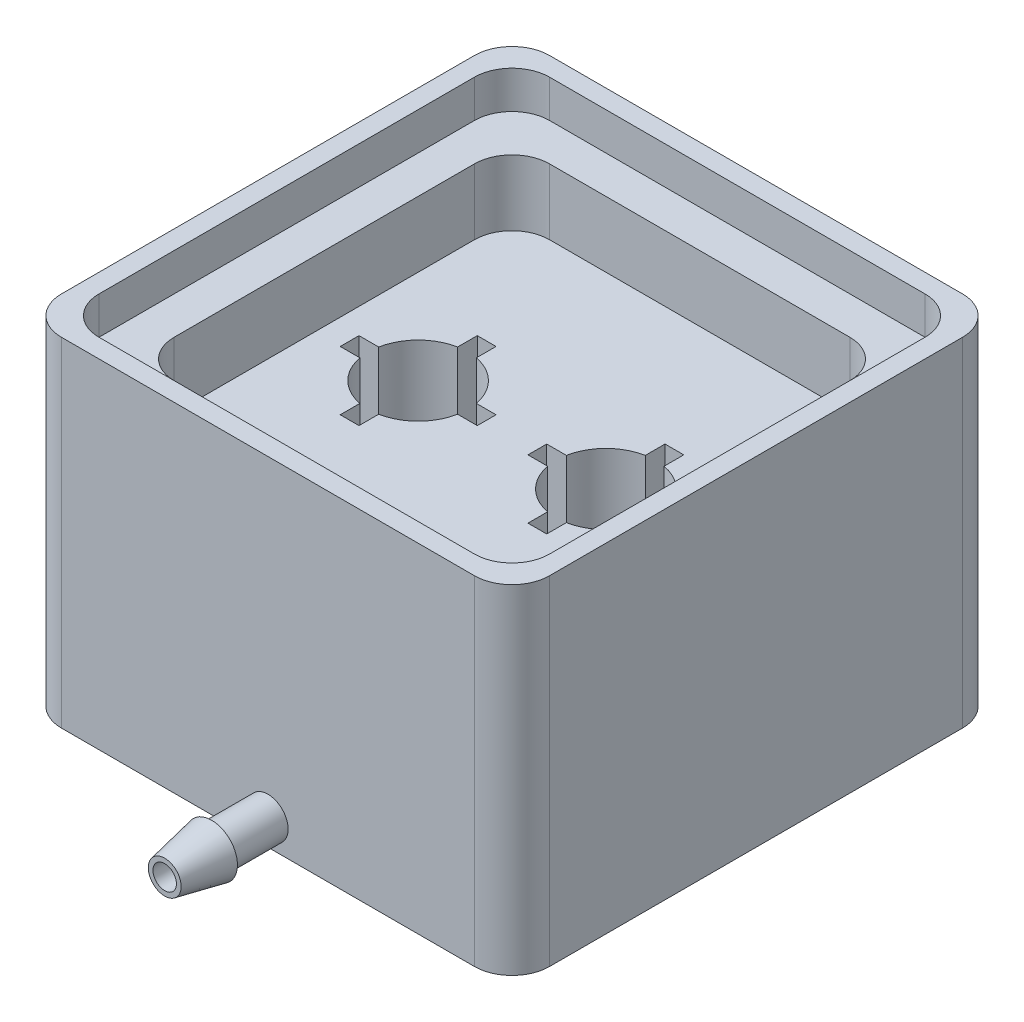
SolidWorks part; units mm, degrees
ref_plane "Front Plane" through (0, 0, 0) normal (0, 0, 1) x (1, 0, 0)
ref_plane "Top Plane" through (0, 0, 0) normal (0, 1, 0) x (1, 0, 0)
ref_plane "Right Plane" through (0, 0, 0) normal (1, 0, 0) x (0, 0, -1)
sketch "Sketch1" plane through (0, 0, 0) normal (0, 1, 0) x (1, 0, 0)
  line L0 (-5, 0) -> (5, 0) construction
  line L1 (-11, -13) -> (11, -13)
  line L2 (-13, -11) -> (-13, 11)
  line L3 (-11, 13) -> (11, 13)
  line L4 (13, -11) -> (13, 11)
  line L5 (-13, -13) -> (13, 13) construction
  line L6 (-13, 13) -> (13, -13) construction
  arc A0 (-13, 11) -> (-11, 13) centre (-11, 11) cw
  arc A1 (11, 13) -> (13, 11) centre (11, 11) cw
  arc A2 (-13, -11) -> (-11, -13) centre (-11, -11) ccw
  arc A3 (13, -11) -> (11, -13) centre (11, -11) cw
  circle A4 centre (5, 0) radius 2.65
  circle A5 centre (-5, 0) radius 2.65
  point P0 (0, 0)
  point P21 (0, 0)
  dimension "D3" = 2
  dimension "D4" = 2
  dimension "D6" = 5.3
  dimension "D7" = 5.3
  dimension "D1" = 26
  dimension "D2" = 26
  dimension "D5" = 10
extrude "Boss-Extrude1" add sketch "Sketch1" along normal blind 12.53
sketch "Sketch2" plane through (0, 12.53, 0) normal (0, 1, 0) x (1, 0, 0)
  line L0 (-5, 0) -> (5, 0) construction
  line L2 (-8.65, -0.5) -> (-1.35, -0.5)
  line L3 (-8.65, -0.5) -> (-8.65, 0.5)
  line L4 (-8.65, 0.5) -> (-1.35, 0.5)
  line L5 (-1.35, -0.5) -> (-1.35, 0.5)
  line L6 (-8.65, -0.5) -> (-1.35, 0.5) construction
  line L7 (-8.65, 0.5) -> (-1.35, -0.5) construction
  line L8 (-5.5, -3.65) -> (-4.5, -3.65)
  line L9 (-5.5, -3.65) -> (-5.5, 3.65)
  line L10 (-5.5, 3.65) -> (-4.5, 3.65)
  line L11 (-4.5, -3.65) -> (-4.5, 3.65)
  line L12 (-5.5, -3.65) -> (-4.5, 3.65) construction
  line L13 (-5.5, 3.65) -> (-4.5, -3.65) construction
  line L14 (4.5, -3.65) -> (5.5, -3.65)
  line L15 (4.5, -3.65) -> (4.5, 3.65)
  line L16 (4.5, 3.65) -> (5.5, 3.65)
  line L17 (5.5, -3.65) -> (5.5, 3.65)
  line L18 (4.5, -3.65) -> (5.5, 3.65) construction
  line L19 (4.5, 3.65) -> (5.5, -3.65) construction
  line L20 (1.35, -0.5) -> (8.65, -0.5)
  line L21 (1.35, -0.5) -> (1.35, 0.5)
  line L22 (1.35, 0.5) -> (8.65, 0.5)
  line L23 (8.65, -0.5) -> (8.65, 0.5)
  line L24 (1.35, -0.5) -> (8.65, 0.5) construction
  line L25 (1.35, 0.5) -> (8.65, -0.5) construction
  point P3 (0, 0)
  circle M15 centre (5, 0) radius 2.65
  circle M16 centre (-5, 0) radius 2.65
  dimension "D1" = 10
  dimension "D2" = 7.3
  dimension "D3" = 7.3
  dimension "D4" = 7.3
  dimension "D5" = 7.3
  dimension "D6" = 1
  dimension "D7" = 1
  dimension "D8" = 1
  dimension "D9" = 1
extrude "Cut-Extrude1" cut sketch "Sketch2" against normal blind 11.785 contours L17 L16 L15 M15 | L20 L23 L22 M15 | L14 L17 L15 M15 | L22 L21 L20 M15 | L2 L5 L4 M16 | L11 L10 L9 M16 | L4 L3 L2 M16 | L8 L11 L9 M16
sketch "Sketch3" plane through (0, 0, 0) normal (1, 0, 0) x (0, 0, -1)
  line L0 (-13, 0.3) -> (-16, 0.3)
  line L1 (-13, 12.53) -> (-13, 0) construction
  line L2 (-16, 0.3) -> (-16, 0)
  line L3 (-16, 0) -> (-18.5, 0.5)
  line L4 (-18.5, 0.5) -> (-18.5, 0.75)
  line L5 (-18.5, 0.75) -> (-13, 0.75)
  line L6 (-13, 0.75) -> (-13, 0.3)
  line L7 (-13, 1.375) -> (-13.6025, 1.375) construction
  line L8 (-11, 0) -> (11, 0) construction
  dimension "D1" = 2.5
  dimension "D2" = 3
  dimension "D3" = 0.875
  dimension "D4" = 1.075
  dimension "D5" = 0.625
  dimension "D6" = 1.375
revolve "Revolve1" add sketch "Sketch3" angle 360 about L7
sketch "Sketch10" plane through (0, 0, 0) normal (1, 0, 0) x (0, 0, -1)
  circle A0 centre (0, 1.375) radius 0.625
extrude "Cut-Extrude3" cut sketch "Sketch10" against normal up to next and the other way up to next
sketch "Sketch5" plane through (0, 0, 13) normal (0, 0, 1) x (1, 0, 0)
  circle A0 centre (0, 1.375) radius 0.625
  dimension "D1" = 1.25
extrude "Cut-Extrude2" cut sketch "Sketch5" against normal up to next
sketch "Sketch6" plane through (0, 12.53, 0) normal (0, 1, 0) x (1, 0, 0)
  line L1 (-11, -13) -> (11, -13)
  line L2 (-13, -11) -> (-13, 11)
  line L3 (-11, 13) -> (11, 13)
  line L4 (13, -11) -> (13, 11)
  line L5 (-13, -13) -> (13, 13) construction
  line L6 (-13, 13) -> (13, -13) construction
  line L7 (-8, -10) -> (8, -10)
  line L8 (-10, -8) -> (-10, 8)
  line L9 (-8, 10) -> (8, 10)
  line L10 (10, -8) -> (10, 8)
  line L11 (-10, -10) -> (10, 10) construction
  line L12 (-10, 10) -> (10, -10) construction
  arc A0 (-13, -11) -> (-11, -13) centre (-11, -11) ccw
  arc A1 (13, -11) -> (11, -13) centre (11, -11) cw
  arc A2 (13, 11) -> (11, 13) centre (11, 11) ccw
  arc A3 (-11, 13) -> (-13, 11) centre (-11, 11) ccw
  arc A4 (-10, -8) -> (-8, -10) centre (-8, -8) ccw
  arc A5 (8, -10) -> (10, -8) centre (8, -8) ccw
  arc A6 (10, 8) -> (8, 10) centre (8, 8) ccw
  arc A7 (-8, 10) -> (-10, 8) centre (-8, 8) ccw
  point P0 (0, 0)
  point P18 (0, 0)
  dimension "D3" = 2
  dimension "D1" = 26
  dimension "D2" = 26
  dimension "D6" = 2
  dimension "D4" = 3
  dimension "D5" = 3
extrude "Boss-Extrude2" add sketch "Sketch6" along normal blind 3.5
sketch "Sketch8" plane through (0, 16.03, 0) normal (0, 1, 0) x (1, 0, 0)
  line L1 (-11, -13) -> (11, -13)
  line L2 (-13, -11) -> (-13, 11)
  line L3 (-11, 13) -> (11, 13)
  line L4 (13, -11) -> (13, 11)
  line L5 (-13, -13) -> (13, 13) construction
  line L6 (-13, 13) -> (13, -13) construction
  line L7 (-10, -12) -> (10, -12)
  line L8 (-12, -10) -> (-12, 10)
  line L9 (-10, 12) -> (10, 12)
  line L10 (12, -10) -> (12, 10)
  line L11 (-12, -12) -> (12, 12) construction
  line L12 (-12, 12) -> (12, -12) construction
  arc A0 (13, 11) -> (11, 13) centre (11, 11) ccw
  arc A1 (13, -11) -> (11, -13) centre (11, -11) cw
  arc A2 (-13, -11) -> (-11, -13) centre (-11, -11) ccw
  arc A3 (-13, 11) -> (-11, 13) centre (-11, 11) cw
  arc A4 (-12, -10) -> (-10, -12) centre (-10, -10) ccw
  arc A5 (10, -12) -> (12, -10) centre (10, -10) ccw
  arc A6 (12, 10) -> (10, 12) centre (10, 10) ccw
  arc A7 (-12, 10) -> (-10, 12) centre (-10, 10) cw
  point P0 (0, 0)
  point P18 (0, 0)
  dimension "D3" = 2
  dimension "D1" = 26
  dimension "D2" = 26
  dimension "D6" = 2
  dimension "D4" = 1
  dimension "D5" = 1
extrude "Boss-Extrude3" add sketch "Sketch8" along normal blind 2
equation "\"D2@Sketch1\"=\"D1@Sketch1\""
equation "\"D7@Sketch1\"=\"D6@Sketch1\""
equation "\"D3@Sketch2\"=\"D2@Sketch2\""
equation "\"D2@Sketch2\"=\"D6@Sketch1\"+2mm"
equation "\"D4@Sketch2\"=\"D2@Sketch2\""
equation "\"D5@Sketch2\"=\"D2@Sketch2\""
equation "\"D7@Sketch2\"=\"D6@Sketch2\""
equation "\"D8@Sketch2\"=\"D6@Sketch2\""
equation "\"D9@Sketch2\"=\"D6@Sketch2\""
equation "\"D1@Sketch6\"=\"D1@Sketch1\""
equation "\"D2@Sketch6\"=\"D1@Sketch1\""
equation "\"D5@Sketch6\"=\"D4@Sketch6\""
equation "\"D1@Sketch8\"=\"D1@Sketch1\""
equation "\"D2@Sketch8\"=\"D1@Sketch1\""
equation "\"D1@Sketch2\"=\"D5@Sketch1\""
